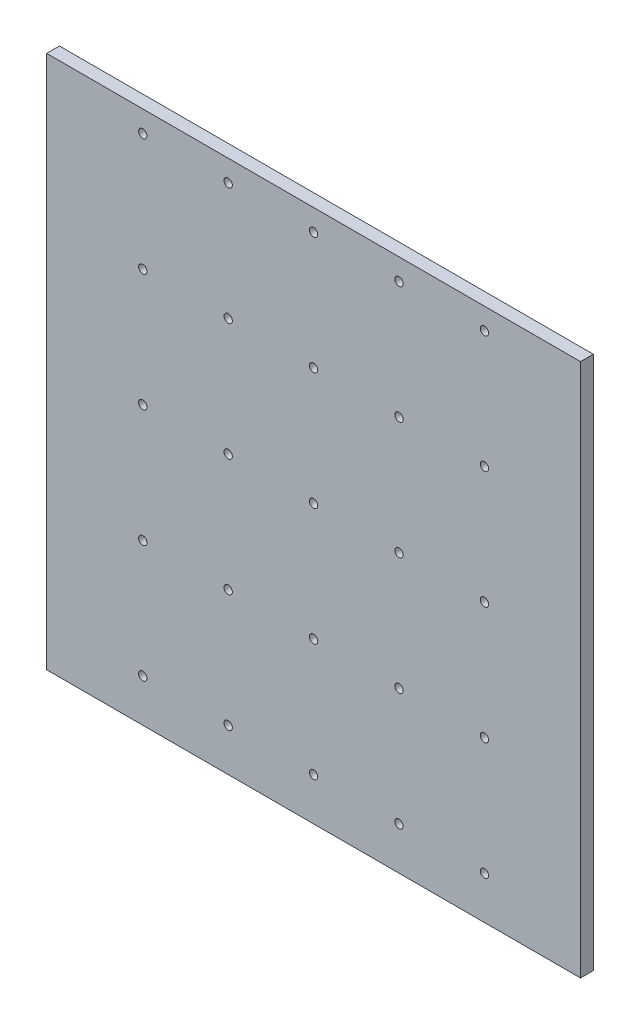
SolidWorks part; units mm, degrees
material "PVC rigide"
ref_plane "Plan de face" through (0, 0, 0) normal (0, 0, 1) x (1, 0, 0)
ref_plane "Plan de dessus" through (0, 0, 0) normal (0, 1, 0) x (1, 0, 0)
ref_plane "Plan de droite" through (0, 0, 0) normal (1, 0, 0) x (0, 0, -1)
sketch "Esquisse1" plane through (0, 0, 0) normal (0, 0, 1) x (1, 0, 0)
  line L1 (0, 0) -> (250, 0)
  line L2 (0, 0) -> (0, 250)
  line L3 (0, 250) -> (250, 250)
  line L4 (250, 0) -> (250, 250)
  dimension "D1" = 250
  dimension "D2" = 250
extrude "Boss.-Extru.1" add sketch "Esquisse1" along normal blind 6 contours L3 L4 L1 L2
hole_wizard "Diamètre du perçage Ø0.15 (0.15)1" positions "Esquisse3" profile "Esquisse4" hole size "Ø0.15" standard "ISO" end condition through all
sketch "Esquisse3" plane through (0, 0, 6) normal (0, 0, 1) x (1, 0, 0)
  line L0 (0, 0) -> (0, 250) construction
  line L1 (0, 0) -> (250, 0) construction
  point P0 (85, 20)
  dimension "D1" = 85
  dimension "D2" = 20
sketch "Esquisse4" plane through (85, 20, 6) normal (1, 0, 0) x (0, -1, 0)
  line L0 (0, 0) -> (0, 6)
  line L1 (0, 6) -> (1.95, 6)
  line L2 (1.95, 6) -> (1.95, 0)
  line L5 (1.95, 0) -> (0, 0)
  line L11 (0, -6.35) -> (0, 107.95) construction
  dimension "Diamètre du perçage jusqu'au prochain" = 3.9
  dimension "Profondeur du perçage jusqu'au prochain" = 6
pattern_linear "Répétition linéaire1" count 4 spacing 40 along (1, 0, 0) count 5 spacing 55 along (0, 1, 0) of "Diamètre du perçage Ø0.15 (0.15)1"
pattern_linear "Répétition linéaire2" count 2 spacing 40 along (-1, 0, 0) count 5 spacing 55 along (0, 1, 0) of "Diamètre du perçage Ø0.15 (0.15)1"
